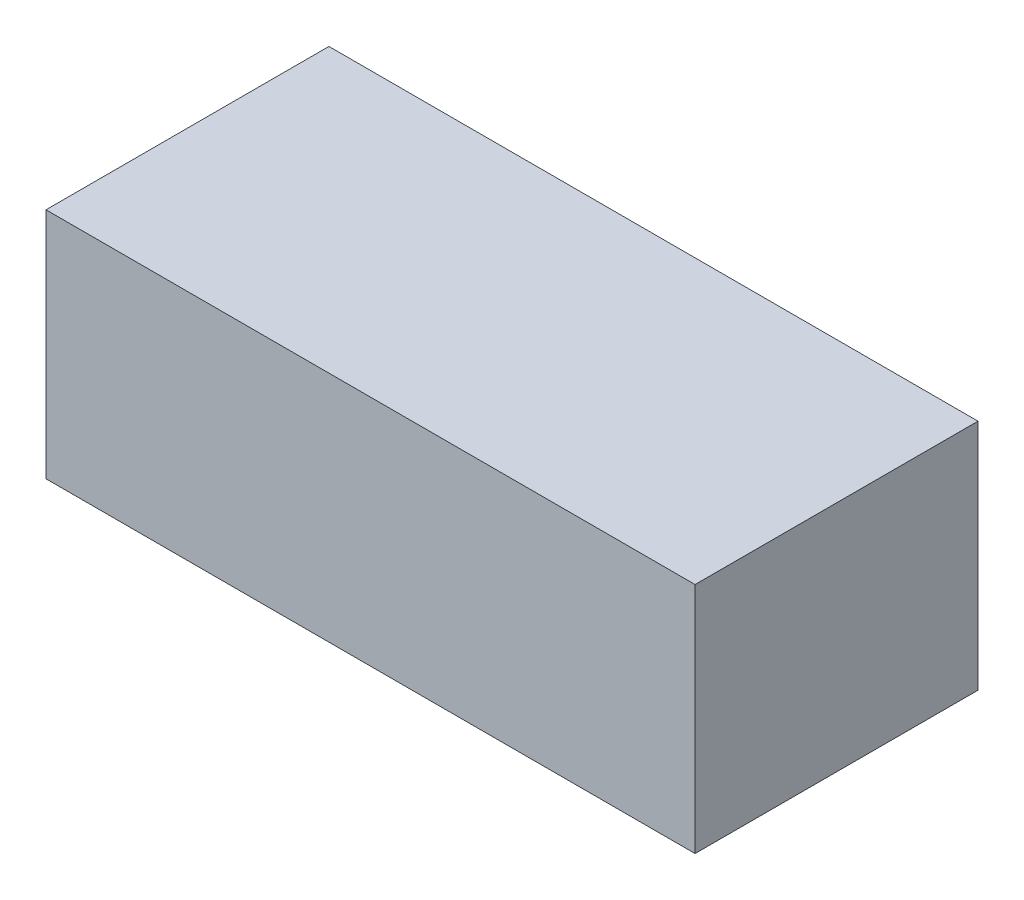
SolidWorks part; units mm, degrees
ref_plane "Front Plane" through (0, 0, 0) normal (0, 0, 1) x (1, 0, 0)
ref_plane "Top Plane" through (0, 0, 0) normal (0, 1, 0) x (1, 0, 0)
ref_plane "Right Plane" through (0, 0, 0) normal (1, 0, 0) x (0, 0, -1)
sketch "Sketch1" plane through (0, 0, 0) normal (0, 1, 0) x (1, 0, 0)
  line L1 (39, -17) -> (-39, -17)
  line L2 (39, -17) -> (39, 17)
  line L3 (39, 17) -> (-39, 17)
  line L4 (-39, -17) -> (-39, 17)
  line L5 (39, -17) -> (-39, 17) construction
  line L6 (39, 17) -> (-39, -17) construction
  point P0 (0, 0)
  dimension "D1" = 78
  dimension "D2" = 34
extrude "Boss-Extrude1" add sketch "Sketch1" along normal blind 28
